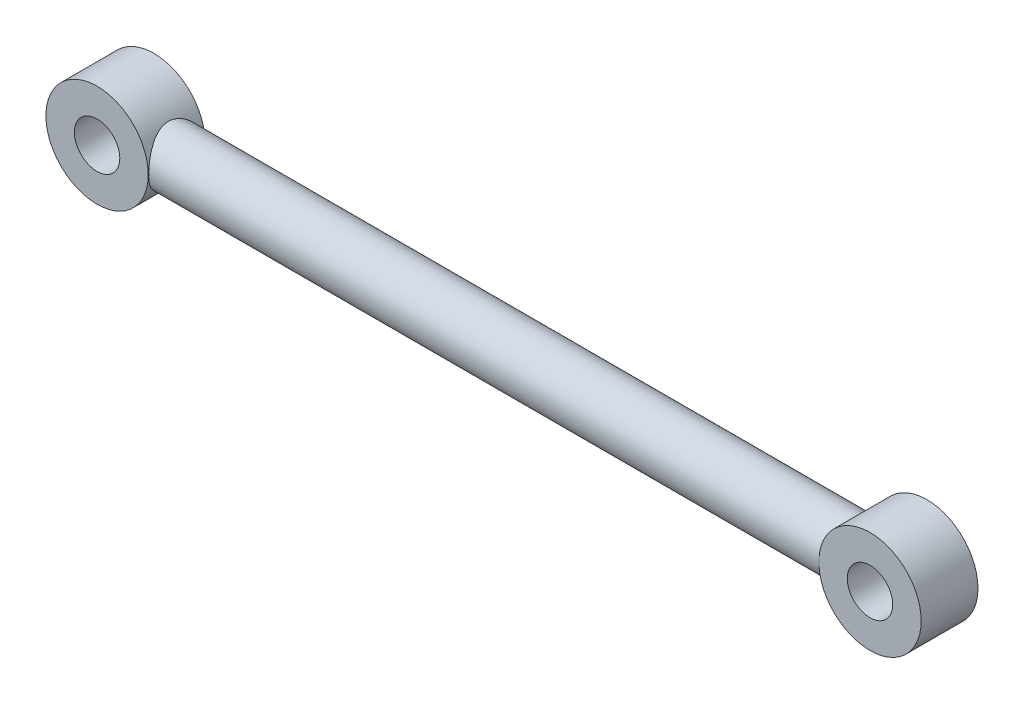
SolidWorks part; units mm, degrees
ref_plane "前视基准面" through (0, 0, 0) normal (0, 0, 1) x (1, 0, 0)
ref_plane "上视基准面" through (0, 0, 0) normal (0, 1, 0) x (1, 0, 0)
ref_plane "右视基准面" through (0, 0, 0) normal (1, 0, 0) x (0, 0, -1)
sketch "草图1" plane through (0, 0, 0) normal (0, 0, 1) x (1, 0, 0)
  line L0 (-34, 0) -> (34, 0)
  circle A0 centre (34, 0) radius 2
  circle A1 centre (-34, 0) radius 2
  circle A2 centre (34, 0) radius 4.5
  circle A3 centre (-34, 0) radius 4.5
extrude "凸台-拉伸1" add sketch "草图1" along normal mid plane 5
sketch "草图2" plane through (0, 0, 0) normal (1, 0, 0) x (0, 0, -1)
  circle A0 centre (0, 0) radius 2.45
extrude "凸台-拉伸2" add sketch "草图2" along normal mid plane 62 separate body
